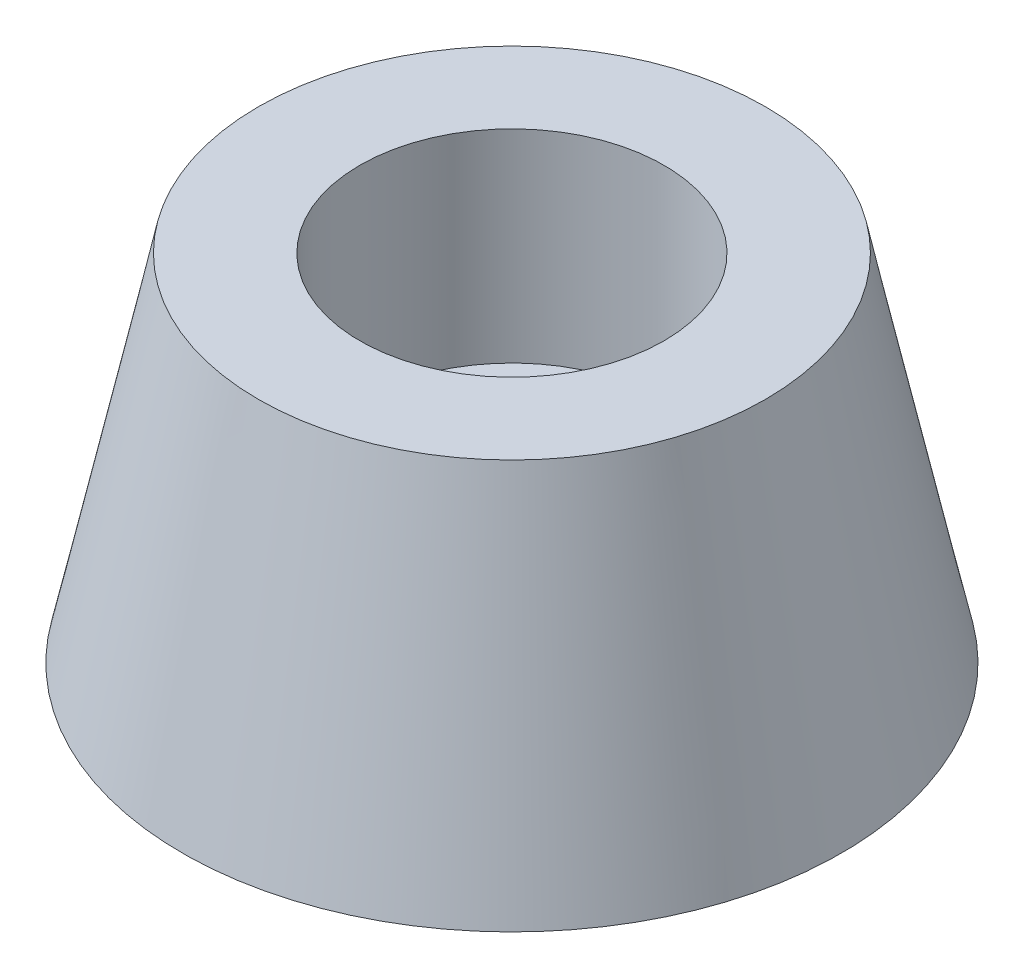
SolidWorks part; units mm, degrees
ref_plane "Front Plane" through (0, 0, 0) normal (0, 0, 1) x (1, 0, 0)
ref_plane "Top Plane" through (0, 0, 0) normal (0, 1, 0) x (1, 0, 0)
ref_plane "Right Plane" through (0, 0, 0) normal (1, 0, 0) x (0, 0, -1)
sketch "Sketch1" plane through (0, 0, 0) normal (0, 0, 1) x (1, 0, 0)
  line L0 (6.5, -7) -> (5, 0)
  line L1 (0, 0) -> (6.5, 0)
  line L2 (0, 0) -> (0, -7)
  line L3 (0, -7) -> (6.5, -7)
  line L4 (6.5, 0) -> (6.5, -7)
  dimension "D1" = 6.5
  dimension "D2" = 5
  dimension "D3" = 7
revolve "Revolve1" add sketch "Sketch1" angle 360 about L2
sketch "Sketch2" plane through (0, 0, 0) normal (0, 1, 0) x (1, 0, 0)
  circle A0 centre (0, 0) radius 1.65
  dimension "D1" = 3.3
extrude "Cut-Extrude1" cut sketch "Sketch2" against normal blind 10
sketch "Sketch3" plane through (0, 0, 0) normal (0, 1, 0) x (1, 0, 0)
  circle A0 centre (0, 0) radius 3
  dimension "D1" = 6
extrude "Cut-Extrude2" cut sketch "Sketch3" against normal blind 4
